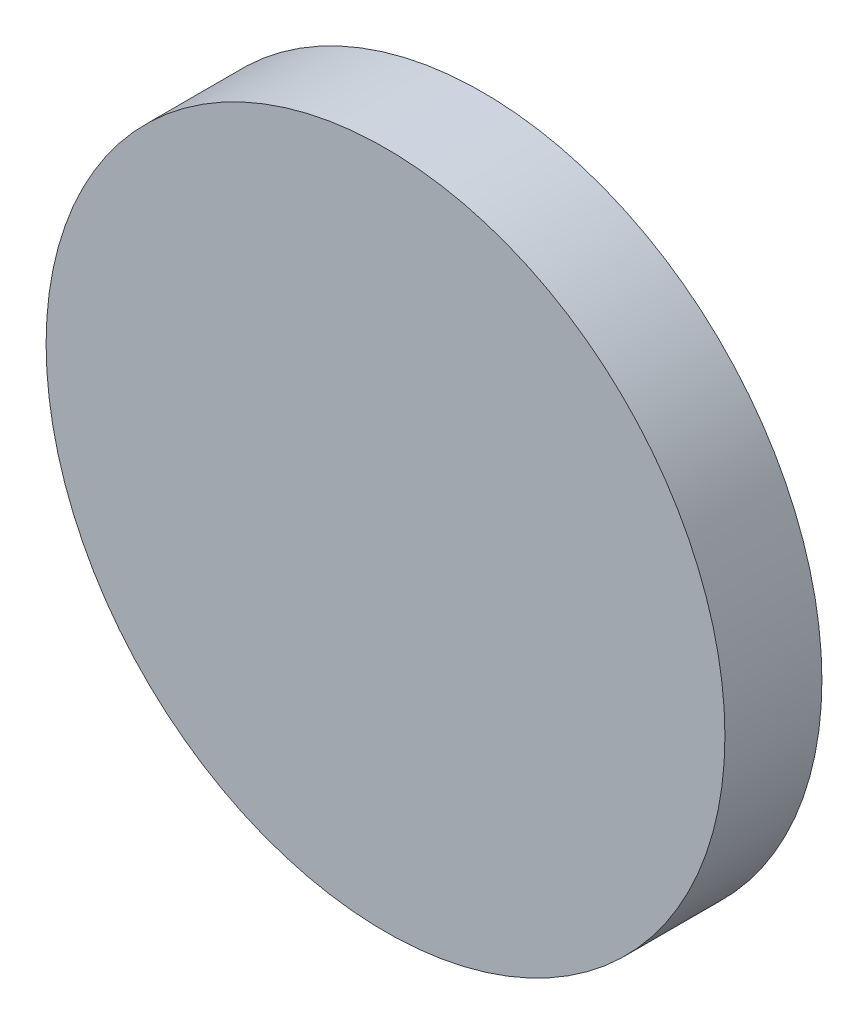
SolidWorks part; units mm, degrees
ref_plane "Plan de face" through (0, 0, 0) normal (0, 0, 1) x (1, 0, 0)
ref_plane "Plan de dessus" through (0, 0, 0) normal (0, 1, 0) x (1, 0, 0)
ref_plane "Plan de droite" through (0, 0, 0) normal (1, 0, 0) x (0, 0, -1)
sketch "Esquisse1" plane through (0, 0, 0) normal (0, 0, 1) x (1, 0, 0)
  circle A0 centre (0, 0) radius 1.4
  dimension "D1" = 2.8
extrude "Boss.-Extru.1" add sketch "Esquisse1" along normal blind 0.4
